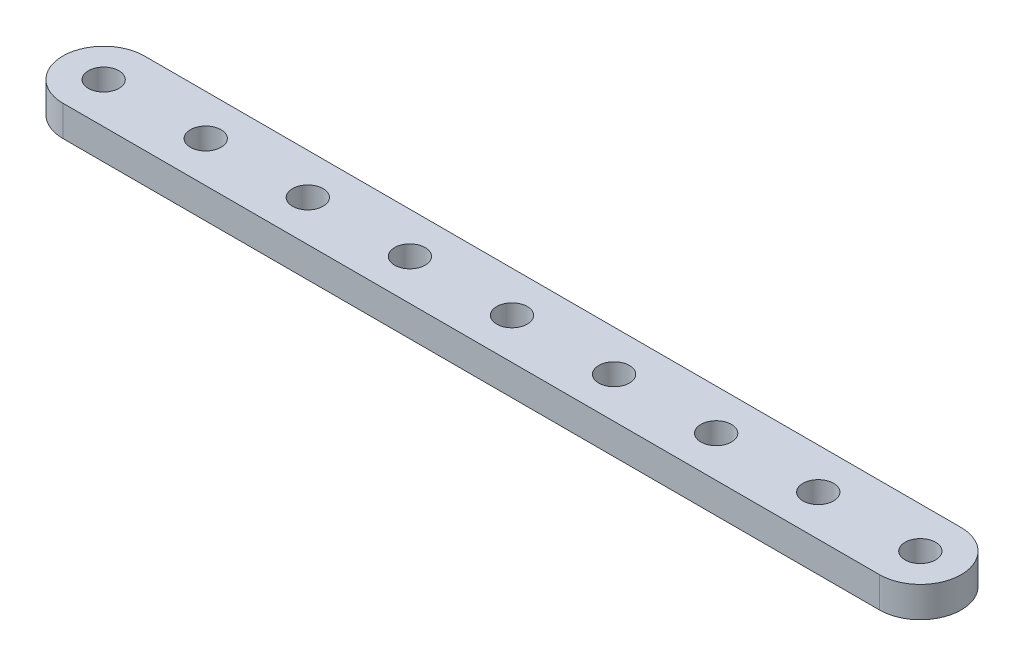
SolidWorks part; units mm, degrees
ref_plane "Front Plane" through (0, 0, 0) normal (0, 0, 1) x (1, 0, 0)
ref_plane "Top Plane" through (0, 0, 0) normal (0, 1, 0) x (1, 0, 0)
ref_plane "Right Plane" through (0, 0, 0) normal (1, 0, 0) x (0, 0, -1)
sketch "Sketch1" plane through (0, 0, 0) normal (0, 1, 0) x (1, 0, 0)
  line L1 (-10, 4) -> (70, 4)
  line L3 (-10, -4) -> (70, -4)
  arc A0 (-10, 4) -> (-10, -4) centre (-10, 0) ccw
  arc A1 (70, 4) -> (70, -4) centre (70, 0) cw
  point P0 (0, 0)
  dimension "D3" = 4
  dimension "End Radius" = 4
  dimension "Centre to centre length" = 80
  dimension "Radius to Origin" = 10
  dimension "Edge to origin" = 4
  dimension "D1" = 4
extrude "Outer Body" add sketch "Sketch1" along normal blind 3 contours L3 A1 L1 A0
sketch "Sketch8" plane through (0, 3, 0) normal (0, 1, 0) x (1, 0, 0)
  line L3 (-10, 4) -> (70, 4) construction
  circle A0 centre (-10, 0) radius 1.5
  circle A1 centre (0, 0) radius 1.5
  circle A2 centre (50, 0) radius 1.5
  circle A3 centre (70, 0) radius 1.5
  circle A4 centre (60, 0) radius 1.5
  circle A6 centre (10, 0) radius 1.5
  circle A7 centre (20, 0) radius 1.5
  circle A8 centre (30, 0) radius 1.5
  circle A9 centre (40, 0) radius 1.5
  dimension "Hole Size" = 3
  dimension "D2" = 3
  dimension "D3" = 3
  dimension "D4" = 3
  dimension "D5" = 3
  dimension "D8" = 3
  dimension "D10" = 3
  dimension "D12" = 3
  dimension "D14" = 3
  dimension "D6" = 10
  dimension "D7" = 10
  dimension "Hole Spacing" = 10
  dimension "D11" = 10
  dimension "D13" = 10
  dimension "D15" = 10
  dimension "D16" = 4
  dimension "Hole Centring" = 4
  dimension "D9" = 4
  dimension "D17" = 4
  dimension "D18" = 4
  dimension "D19" = 4
extrude "Holes" cut sketch "Sketch8" against normal through all
equation "\"D3@Sketch1\"=\"End Radius@Sketch1\""
equation "\"D2@Sketch8\"=\"Hole Size@Sketch8\""
equation "\"D8@Sketch8\"=\"Hole Size@Sketch8\""
equation "\"D10@Sketch8\"=\"Hole Size@Sketch8\""
equation "\"D12@Sketch8\"=\"Hole Size@Sketch8\""
equation "\"D14@Sketch8\"=\"Hole Size@Sketch8\""
equation "\"D3@Sketch8\"=\"Hole Size@Sketch8\""
equation "\"D4@Sketch8\"=\"Hole Size@Sketch8\""
equation "\"D5@Sketch8\"=\"Hole Size@Sketch8\""
equation "\"D11@Sketch8\"=\"Hole Spacing@Sketch8\""
equation "\"D13@Sketch8\"=\"Hole Spacing@Sketch8\""
equation "\"D15@Sketch8\"=\"Hole Spacing@Sketch8\""
equation "\"D7@Sketch8\"=\"Hole Spacing@Sketch8\""
equation "\"D6@Sketch8\"=\"Hole Spacing@Sketch8\""
equation "\"D9@Sketch8\"=\"Hole Centring@Sketch8\""
equation "\"D17@Sketch8\"=\"Hole Centring@Sketch8\""
equation "\"D18@Sketch8\"=\"Hole Centring@Sketch8\""
equation "\"D19@Sketch8\"=\"Hole Centring@Sketch8\""
equation "\"D16@Sketch8\"=\"Hole Centring@Sketch8\""
equation "\"D1@Sketch1\"=\"Edge to origin@Sketch1\""
